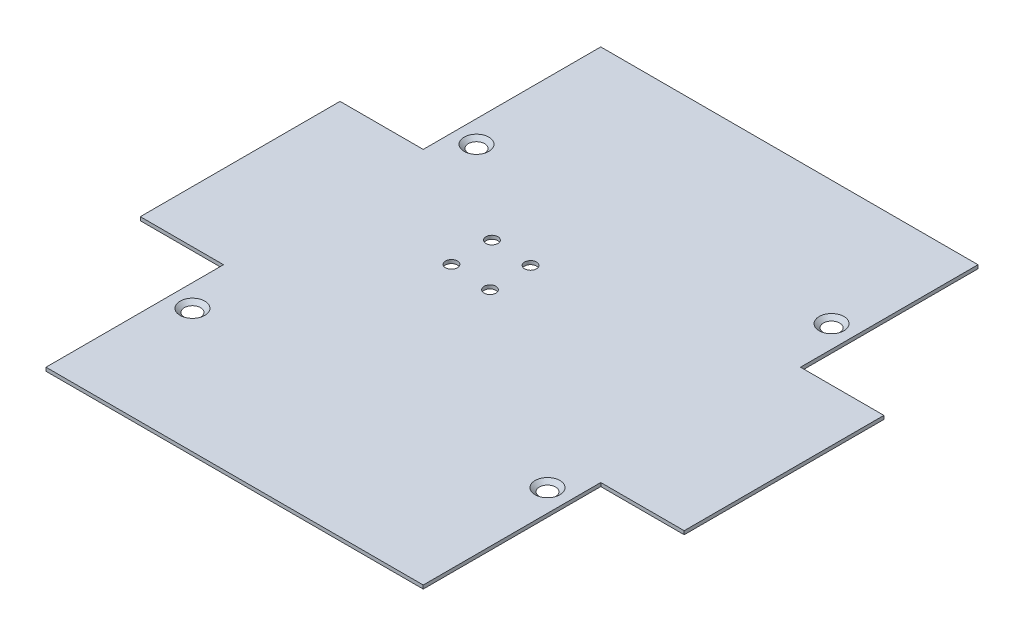
SolidWorks part; units mm, degrees
material "1023 Carbon Steel Sheet (SS)"
ref_plane "Front Plane" through (0, 0, 0) normal (0, 0, 1) x (1, 0, 0)
ref_plane "Top Plane" through (0, 0, 0) normal (0, 1, 0) x (1, 0, 0)
ref_plane "Right Plane" through (0, 0, 0) normal (1, 0, 0) x (0, 0, -1)
sketch "Sketch1" plane through (0, 0, 0) normal (0, 1, 0) x (1, 0, 0)
  line L0 (-107.95, 50.8) -> (-131.7625, 50.8)
  line L1 (0, 0) -> (-107.95, 0)
  line L2 (0, 0) -> (0, 50.8)
  line L3 (0, 158.75) -> (-107.95, 158.75)
  line L4 (-107.95, 0) -> (-107.95, 50.8)
  line L6 (-131.7625, 50.8) -> (-131.7625, 107.95)
  line L7 (-131.7625, 107.95) -> (-107.95, 107.95)
  line L8 (0, 107.95) -> (23.876, 107.95)
  line L9 (23.876, 50.8) -> (0, 50.8)
  line L10 (23.876, 107.95) -> (23.876, 50.8)
  line L12 (0, 107.95) -> (0, 158.75)
  line L13 (-107.95, 107.95) -> (-107.95, 158.75)
  dimension "D1" = 107.95
  dimension "D2" = 158.75
  dimension "D3" = 50.8
  dimension "D5" = 23.876
  dimension "D6" = 57.15
  dimension "D7" = 131.7625
extrude "Boss-Extrude1" add sketch "Sketch1" along normal blind 1.016
hole_wizard "CSK for #6 Flat Head Machine Screw (100)1" positions "Sketch3" profile "Sketch2" countersink size "#6" standard "ANSI Inch" end condition through all
sketch "Sketch3" plane through (0, 1.016, 0) normal (0, 1, 0) x (1, 0, 0)
  line L0 (-107.95, 50.8) -> (-107.95, 0) construction
  line L1 (0, 158.75) -> (-107.95, 158.75) construction
  line L2 (-107.95, 0) -> (0, 0) construction
  line L3 (0, 0) -> (0, 50.8) construction
  point P0 (-101.6, 116.84)
  point P2 (-6.35, 123.19)
  point P4 (-6.35, 41.91)
  point P6 (-101.6, 35.56)
  dimension "D1" = 6.35
  dimension "D2" = 41.91
  dimension "D3" = 35.56
  dimension "D4" = 35.56
  dimension "D5" = 41.91
  dimension "D6" = 6.35
  dimension "D7" = 6.35
  dimension "D8" = 6.35
sketch "Sketch2" plane through (-101.6, 1.016, -116.84) normal (1, 0, 0) x (0, 0, 1)
  line L0 (0, 0) -> (0, 1.016)
  line L1 (0, 1.016) -> (1.8986, 1.016)
  line L2 (1.8986, 1.016) -> (1.8986, 1.38)
  line L3 (1.8986, 1.38) -> (3.5433, 0)
  line L5 (3.5433, 0) -> (0, 0)
  line L6 (-1.8986, 1.38) -> (-3.5433, 0) construction
  line L11 (0, -6.35) -> (0, 107.95) construction
  dimension "Thru Hole Dia." = 3.7973
  dimension "Thru Hole Depth" = 1.016
  dimension "Near C'Sink Dia." = 7.0866
  dimension "Near C'Sink Angle" = 100
hole_wizard "M3 Clearance Hole1" positions "Sketch5" profile "Sketch4" hole size "M3" standard "ANSI Metric"
sketch "Sketch5" plane through (0, 1.016, 0) normal (0, 1, 0) x (1, 0, 0)
  point P0 (-63.847, 94.5485)
  point P3 (-63.6212, 82.7316)
  point P6 (-75.6413, 95.3124)
  point P9 (-75.4155, 83.4955)
sketch "Sketch4" plane through (-63.847, 1.016, -94.5485) normal (1, 0, 0) x (0, 0, 1)
  line L0 (0, 0) -> (0, 21.0875)
  line L1 (0, 21.0875) -> (1.7, 20.066)
  line L2 (1.7, 20.066) -> (1.7, 0)
  line L5 (1.7, 0) -> (0, 0)
  line L10 (0, 21.0875) -> (-1.7, 20.066) construction
  line L11 (0, -6.35) -> (0, 107.95) construction
  dimension "Hole Dia." = 3.4
  dimension "Hole Depth" = 20.066
  dimension "Drill Angle" = 118
equation "\"D7@Sketch3\"=\"D1@Sketch3\""
equation "\"D8@Sketch3\"=\"D1@Sketch3\""
equation "\"D5@Sketch1\"=(6.13-\"D1@Sketch1\")/2"
